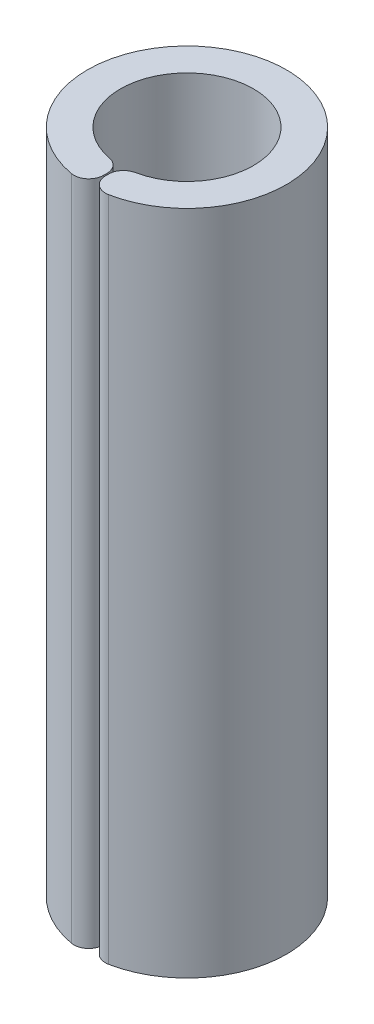
SolidWorks part; units mm, degrees
ref_plane "Front" through (0, 0, 0) normal (0, 0, 1) x (1, 0, 0)
ref_plane "Top" through (0, 0, 0) normal (0, 1, 0) x (1, 0, 0)
ref_plane "Right" through (0, 0, 0) normal (1, 0, 0) x (0, 0, -1)
sketch "Sketch1" plane through (0, 0, 0) normal (0, 1, 0) x (1, 0, 0)
  line L0 (0, 0) -> (0, -4) construction
  line L1 (0, 0) -> (0.0698, -3.9994) construction
  line L2 (0.0467, -2.6746) -> (0.0698, -3.9994)
  line L3 (0, -2.675) -> (0, -4)
  circle A0 centre (0, 0) radius 4 construction
  circle A1 centre (0, 0) radius 2.675 construction
  arc A2 (0.0467, -2.6746) -> (0, -2.675) centre (0, 0) ccw
  arc A3 (0.0698, -3.9994) -> (0, -4) centre (0, 0) ccw
  dimension "D1" = 5.35
  dimension "D2" = 8
  dimension "D3" = 1
extrude "Boss-Extrude1" add sketch "Sketch1" along normal blind 26.8
fillet "Fillet1" radius 0.6 4 edges at (0.0698, 13.4, 3.9994) (0, 13.4, 4) (0.0467, 13.4, 2.6746) (0, 13.4, 2.675)
